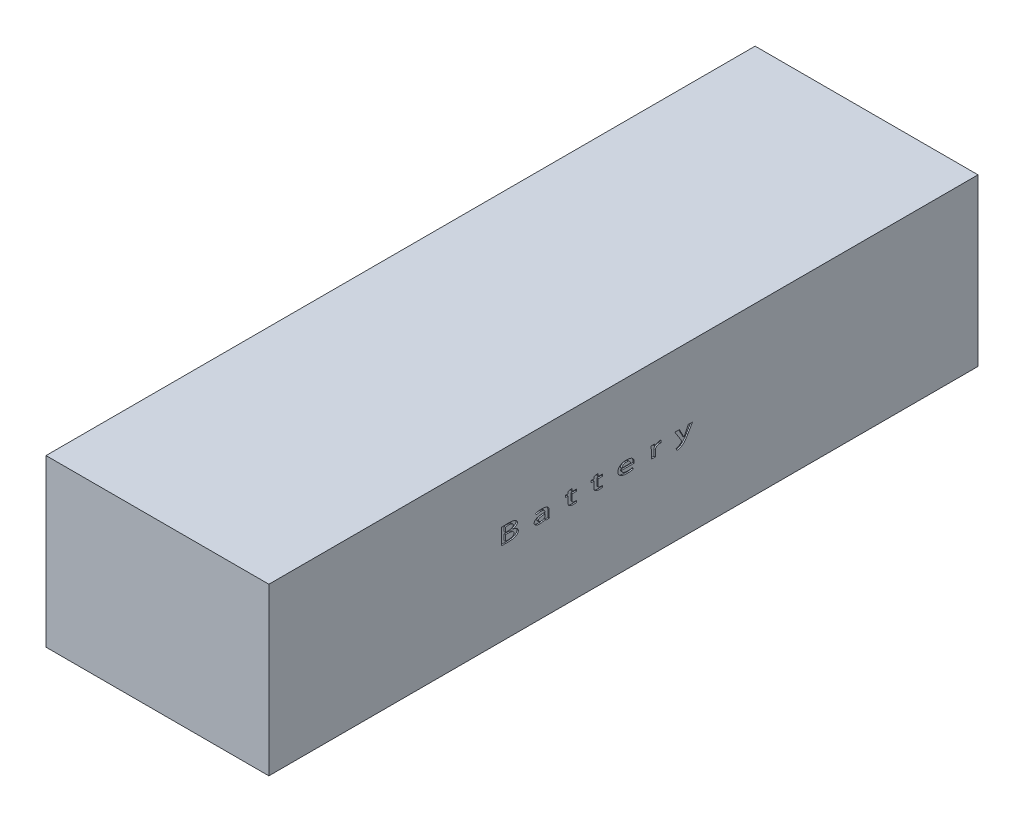
SolidWorks part; units mm, degrees
ref_plane "Front Plane" through (0, 0, 0) normal (0, 0, 1) x (1, 0, 0)
ref_plane "Top Plane" through (0, 0, 0) normal (0, 1, 0) x (1, 0, 0)
ref_plane "Right Plane" through (0, 0, 0) normal (1, 0, 0) x (0, 0, -1)
sketch "Sketch1" plane through (0, 0, 0) normal (0, 1, 0) x (1, 0, 0)
  line L1 (-24.4273, 40.1665) -> (19.5726, 40.1665)
  line L2 (-24.4273, 40.1665) -> (-24.4273, -99.8334)
  line L3 (-24.4273, -99.8334) -> (19.5726, -99.8334)
  line L4 (19.5726, 40.1665) -> (19.5726, -99.8334)
  dimension "D1" = 43.9999
  dimension "D2" = 140
extrude "Boss-Extrude1" add sketch "Sketch1" along normal blind 32.766
sketch "Sketch2" plane through (19.5726, 0, 0) normal (1, 0, 0) x (0, 0, -1)
  line L0 (-99.8334, 16.383) -> (40.1665, 16.383) construction
  line L1 (-99.8334, 32.766) -> (-99.8334, 0) construction
  line L2 (40.1665, 32.766) -> (40.1665, 0) construction
  text T0 "           Battery" font "Adobe Fan Heiti Std B" height 3.175
extrude "Cut-Extrude1" cut sketch "Sketch2" against normal blind 0.254
